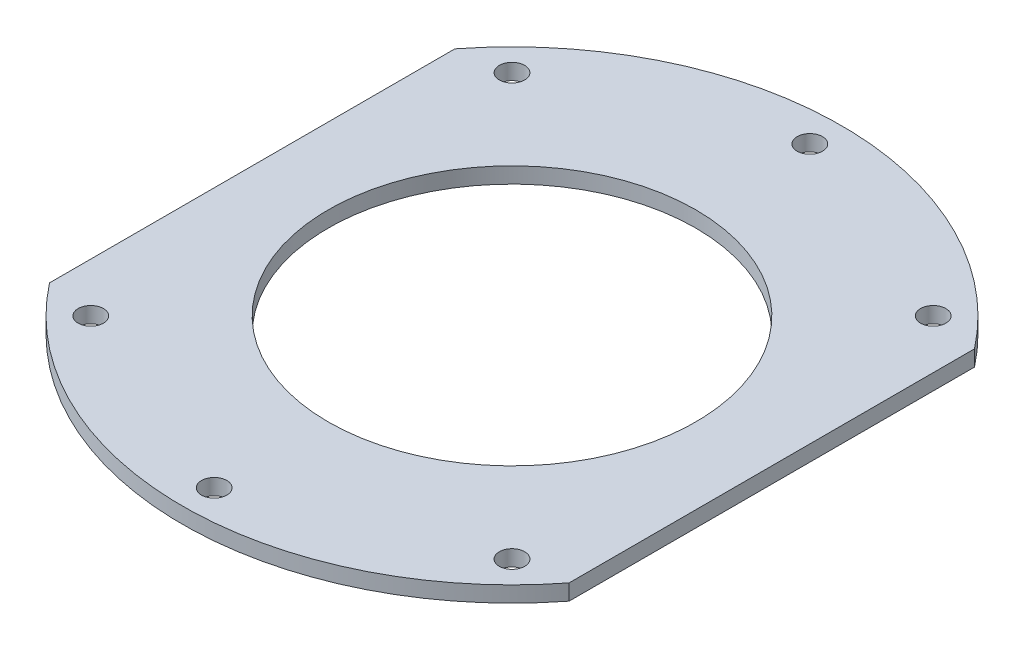
SolidWorks part; units mm, degrees
ref_plane "前视基准面" through (0, 0, 0) normal (0, 0, 1) x (1, 0, 0)
ref_plane "上视基准面" through (0, 0, 0) normal (0, 1, 0) x (1, 0, 0)
ref_plane "右视基准面" through (0, 0, 0) normal (1, 0, 0) x (0, 0, -1)
sketch "草图1" plane through (0, 0, 0) normal (0, 1, 0) x (1, 0, 0)
  circle A0 centre (0, 0) radius 29
  circle A1 centre (0, 0) radius 52
  circle A2 centre (47, 0) radius 2
  circle A3 centre (33.234, -33.234) radius 2
  circle A4 centre (0, -47) radius 2
  circle A5 centre (-33.234, -33.234) radius 2
  circle A6 centre (-47, 0) radius 2
  circle A7 centre (-33.234, 33.234) radius 2
  circle A8 centre (0, 47) radius 2
  circle A9 centre (33.234, 33.234) radius 2
  circle A10 centre (0, 0) radius 43 construction
  point P6 (52, 0)
  point P9 (43, 0)
  dimension "D1" = 58
  dimension "D2" = 86
  dimension "D3" = 4
  dimension "D4" = 4
  dimension "D7" = 5
  dimension "D5" = 8
extrude "凸台-拉伸1" add sketch "草图1" along normal blind 2.5
sketch "草图2" plane through (0, 2.5, 0) normal (0, 1, 0) x (1, 0, 0)
  line L1 (-41, -55.0176) -> (41, -55.0176)
  line L2 (-41, -55.0176) -> (-41, 55.0176)
  line L3 (-41, 55.0176) -> (41, 55.0176)
  line L4 (41, -55.0176) -> (41, 55.0176)
  line L5 (-41, -55.0176) -> (41, 55.0176) construction
  line L6 (-41, 55.0176) -> (41, -55.0176) construction
  point P0 (0, 0)
  dimension "D1" = 82
extrude "切除-拉伸-薄壁1" cut sketch "草图2" against normal blind 4 thin
